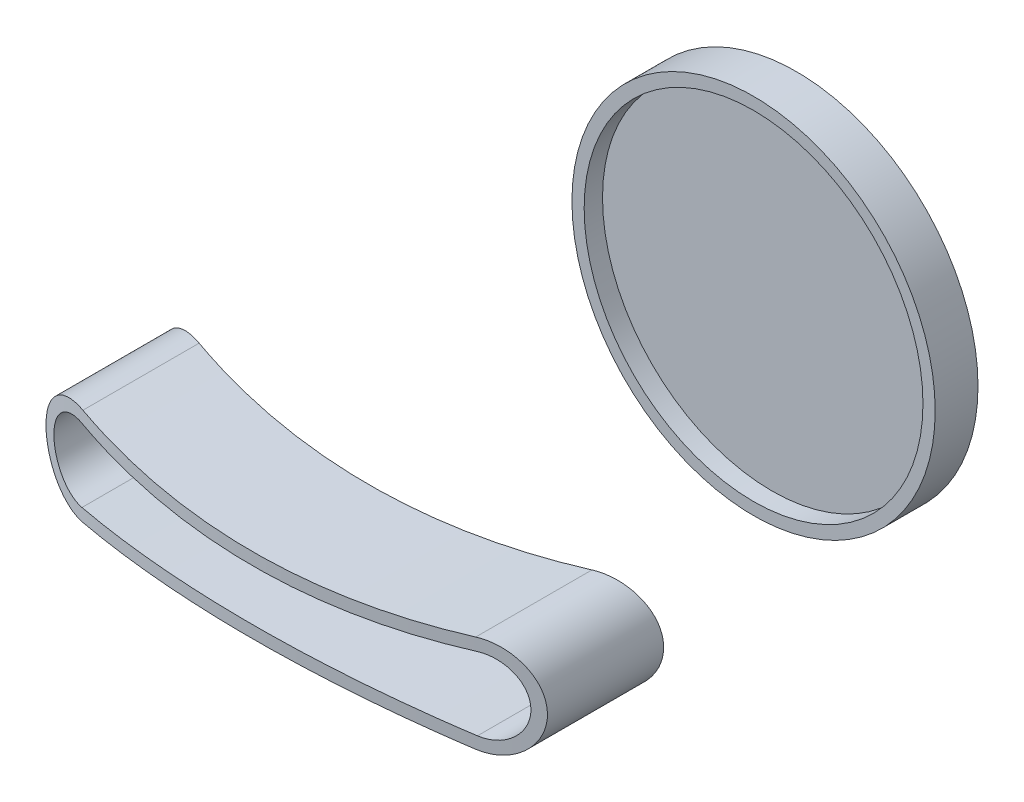
SolidWorks part; units mm, degrees
ref_plane "Front Plane" through (0, 0, 0) normal (0, 0, 1) x (1, 0, 0)
ref_plane "Top Plane" through (0, 0, 0) normal (0, 1, 0) x (1, 0, 0)
ref_plane "Right Plane" through (0, 0, 0) normal (1, 0, 0) x (0, 0, -1)
sketch "Sketch1" plane through (0, 0, 0) normal (0, 0, 1) x (1, 0, 0)
  line L0 (0, 0) -> (0, 27147.7923) construction
  line L1 (0, 0) -> (-27147.7923, 0) construction
  circle A0 centre (0, 0) radius 29.7
  dimension "D1" = 59.4
extrude "Boss-Extrude1" add sketch "Sketch1" along normal blind 7
ref_plane "Plane1" through (0, 0, 82.7) normal (0, 0, 1) x (1, 0, 0)
sketch "Sketch2" plane through (0, 0, 82.7) normal (0, 0, 1) x (1, 0, 0)
  line L0 (0, 0) -> (-50000, 0) construction
  line L1 (0, 0) -> (0, 50000) construction
  arc A0 (32.1141, -7.9508) -> (32.1141, 7.9508) centre (33, 0) ccw
  arc A1 (-32.1141, -7.9508) -> (-32.1141, 7.9508) centre (-33, 0) cw
  arc A2 (-32.1141, 7.9508) -> (32.1141, 7.9508) centre (0, 296.1672) ccw
  arc A3 (-32.1141, -7.9508) -> (32.1141, -7.9508) centre (0, -296.1672) cw
  arc A4 (-32.3356, 5.9631) -> (32.3356, 5.9631) centre (0, 296.1672) ccw
  arc A5 (32.3356, -5.9631) -> (32.3356, 5.9631) centre (33, 0) ccw
  arc A6 (-32.3356, -5.9631) -> (32.3356, -5.9631) centre (0, -296.1672) cw
  arc A7 (-32.3356, -5.9631) -> (-32.3356, 5.9631) centre (-33, 0) cw
  dimension "D1" = 16
  dimension "D3" = 290
  dimension "D2" = 33
  dimension "D4" = 2
extrude "Boss-Extrude2" add sketch "Sketch2" along normal mid plane 40 separate body
sketch "Sketch3" plane through (0, 0, 0) normal (0, 1, 0) x (1, 0, 0)
  line L0 (-41, -82.7) -> (41, -82.7) construction
  line L1 (-41, -62.7) -> (-41, -102.7) construction
  line L2 (41, -102.7) -> (41, -62.7) construction
  line L3 (-41, -82.7) -> (-41, -81.7) construction
  line L4 (-41, -81.7) -> (41, -81.7) construction
  line L5 (41, -81.7) -> (41, -82.7) construction
  line L6 (-41, -81.7) -> (-41, -62.7) construction
  line L7 (-41, -81.7) -> (-41, -62.7)
  line L8 (41, -81.7) -> (41, -62.7)
  line L9 (-41, -81.7) -> (-81.4491, -125.0767)
  line L10 (-81.4491, -125.0767) -> (16.8728, -172.1846)
  line L11 (16.8728, -172.1846) -> (103.064, -103.3883)
  line L12 (103.064, -103.3883) -> (41, -81.7)
  line L13 (-41, -62.7) -> (13.3408, -29.6794)
  line L14 (13.3408, -29.6794) -> (58.3969, -46.1897)
  line L15 (58.3969, -46.1897) -> (41, -62.7)
  arc A0 (-41, -81.7) -> (41, -81.7) centre (0, 31.0785) ccw
  arc A1 (-41, -62.7) -> (41, -62.7) centre (0, 50.0785) ccw
  dimension "D1" = 120
  dimension "D3" = 120
  dimension "D2" = 19
extrude "Cut-Extrude1" cut sketch "Sketch3" against normal mid plane 40 contours A0 L9 L10 L11 L12 | L13 A1 L15 L14
sketch3d "3DSketch2"
  circle A0 centre (0, 0, 7) radius 29.7 construction
  spline S0 degree 2 poles (-0.4941, -29.6959, 7) (0.0701, -27.6962, 41.7548) (-0.1969, -6.1672, 69.9213) knots 0 0 0 1 1 1
  spline S2 degree 2 poles (-29.7, 0, 7) (-46.029, 0, 32.7787) (-41, 0, 62.7) knots 0 0 0 1 1 1
  spline S3 degree 3 poles (-32.1141, 7.9508, 65.5445) (-32.6701, 8.0127, 65.3901) (-33.2213, 8.0158, 65.2326) (-34.0416, 7.9367, 64.9921) (-34.3138, 7.8962, 64.9112) (-34.8562, 7.7866, 64.748) (-35.1266, 7.7171, 64.6655) (-35.9167, 7.4698, 64.4217) (-36.4212, 7.2526, 64.262) (-37.145, 6.848, 64.028) (-37.3819, 6.699, 63.9506) (-37.8381, 6.3773, 63.8) (-38.0565, 6.2055, 63.7272) (-38.683, 5.6578, 63.5164) (-39.0629, 5.25, 63.3861) (-39.5726, 4.5697, 63.2089) (-39.7309, 4.333, 63.1534) (-40.0196, 3.8478, 63.0517) (-40.282, 3.3483, 62.9586) (-40.4919, 2.8202, 62.8835) (-40.6744, 2.2773, 62.8179) (-40.752, 1.9973, 62.7899) (-40.9367, 1.1565, 62.7231) (-40.9991, 0.5882, 62.7003) (-41.0004, -0.276, 62.6998) (-40.985, -0.5675, 62.7054) (-40.9236, -1.1403, 62.7278) (-40.8317, -1.7056, 62.7611) (-40.6805, -2.2566, 62.8157) (-40.4994, -2.8002, 62.8808) (-40.3933, -3.0694, 62.9188) (-40.0375, -3.8469, 63.0456) (-39.7493, -4.332, 63.1474) (-39.2425, -5.0111, 63.3237) (-39.0603, -5.2299, 63.3866) (-38.6791, -5.6415, 63.5171) (-38.2792, -6.03, 63.6529) (-37.843, -6.3736, 63.7984) (-37.3885, -6.6947, 63.9485) (-37.1509, -6.8445, 64.0261) (-36.4246, -7.2512, 64.2609) (-35.9194, -7.4687, 64.4208) (-35.1304, -7.716, 64.6643) (-34.8609, -7.7855, 64.7465) (-34.317, -7.8957, 64.9103) (-34.044, -7.9364, 64.9914) (-33.2221, -8.0158, 65.2324) (-32.6702, -8.0128, 65.39) (-32.1141, -7.9508, 65.5445) knots 0 0 0 0 0.0625 0.0625 0.09375 0.09375 0.125 0.125 0.1875 0.1875 0.21875 0.21875 0.25 0.25 0.3125 0.3125 0.34375 0.34375 0.375 0.40625 0.40625 0.4375 0.4375 0.5 0.5 0.53125 0.53125 0.5625 0.59375 0.59375 0.625 0.625 0.6875 0.6875 0.71875 0.71875 0.75 0.78125 0.78125 0.8125 0.8125 0.875 0.875 0.90625 0.90625 0.9375 0.9375 1 1 1 1 construction
  spline S4 degree 2 poles (29.7, 0, 7) (46.029, 0, 32.7787) (41, 0, 62.7) knots 0 0 0 1 1 1
  spline S6 degree 3 poles (-32.1141, -7.9508, 65.5445) (-26.8739, -7.3669, 66.9999) (-21.5851, -6.9222, 68.087) (-10.9124, -6.3233, 69.5456) (-5.5284, -6.169, 69.9171) (1.2629, -6.1668, 69.9225) (2.6243, -6.1758, 69.9005) (5.3532, -6.2134, 69.8098) (6.7202, -6.2419, 69.7409) (10.8012, -6.3556, 69.4655) (13.5049, -6.4693, 69.1899) (21.5658, -6.9201, 68.0922) (26.8732, -7.3668, 67.0001) (32.1141, -7.9508, 65.5445) knots 0 0 0 0 0.25 0.25 0.5 0.5 0.5625 0.5625 0.625 0.625 0.75 0.75 1 1 1 1 construction
  spline S7 degree 2 poles (-0.4941, 29.6959, 7) (0.0701, 27.6962, 41.7548) (-0.1969, 6.1672, 69.9213) knots 0 0 0 1 1 1
  point P4 (0, 0, 0)
  point P8 (0, 0, 36.7)
  point P15 (-0.4941, -29.6959, 7)
sketch "Sketch4" plane through (0, 0, 7) normal (0, 0, 1) x (1, 0, 0)
  circle A0 centre (0, 0) radius 27.7
  circle A1 centre (0, 0) radius 29.7
  dimension "D1" = 55.4
extrude "Cut-Extrude2" cut sketch "Sketch4" against normal blind 3 contours A0
